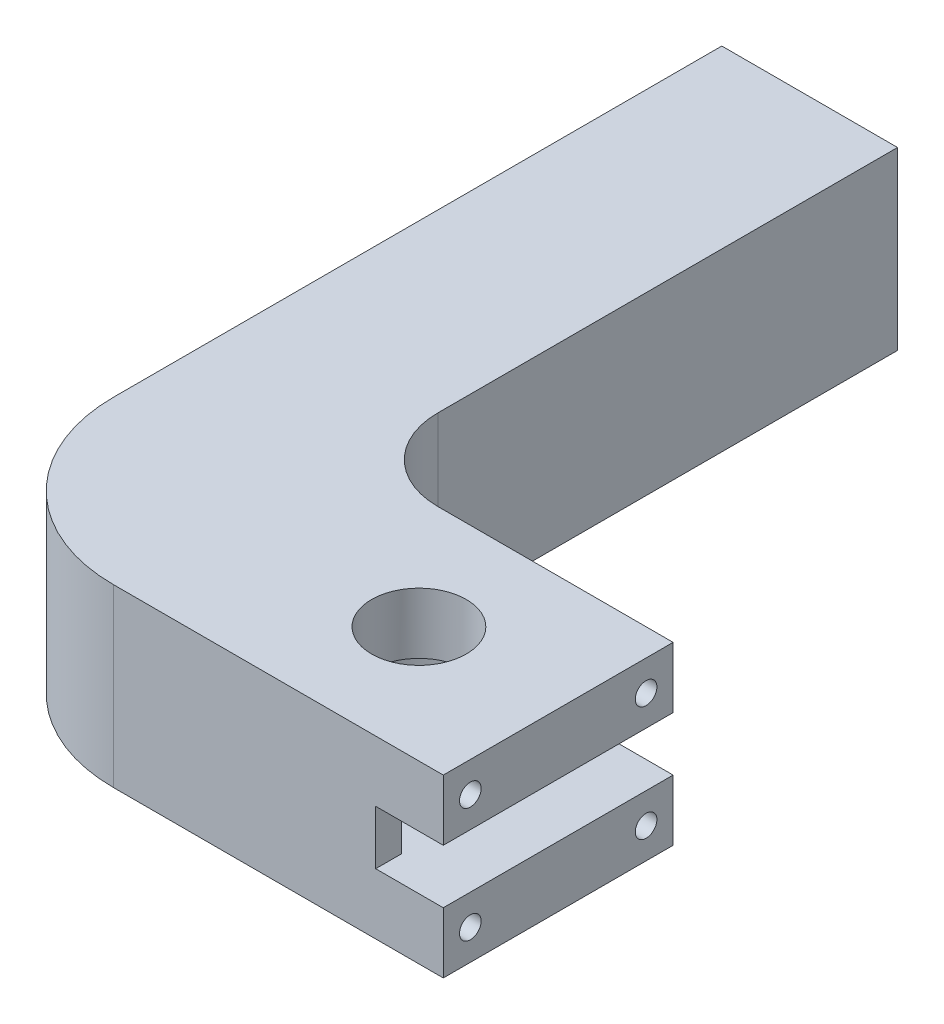
SolidWorks part; units mm, degrees
ref_plane "Front Plane" through (0, 0, 0) normal (0, 0, 1) x (1, 0, 0)
ref_plane "Top Plane" through (0, 0, 0) normal (0, 1, 0) x (1, 0, 0)
ref_plane "Right Plane" through (0, 0, 0) normal (1, 0, 0) x (0, 0, -1)
ref_plane "Plane1" through (0, 571.5, 0) normal (0, 1, 0) x (1, 0, 0)
sketch "Sketch1" plane through (0, 571.5, 0) normal (0, 1, 0) x (1, 0, 0)
  line L0 (3987.8, -7239) -> (3987.8, -5080)
  line L1 (3987.8, -5080) -> (0, -5080)
  line L2 (0, -5080) -> (0, -7239)
  line L3 (0, -7239) -> (3987.8, -7239)
extrude "Boss-Extrude1" add sketch "Sketch1" against normal blind 571.5
sketch "Sketch2" plane through (0, 571.5, 0) normal (0, 1, 0) x (-1, 0, 0)
  line L0 (-3987.8, 5321.3) -> (-3447.3581, 5321.3)
  line L1 (-3302, 6985) -> (-3987.8, 6985)
  line L2 (-3987.8, 6985) -> (-3987.8, 7239)
  line L3 (-3987.8, 7239) -> (0, 7239)
  line L4 (0, 7239) -> (0, 5080)
  line L5 (0, 5080) -> (-3987.8, 5080)
  line L6 (-3987.8, 5080) -> (-3987.8, 5321.3)
  arc A0 (-3447.3581, 5321.3) -> (-3302, 6985) centre (-3302, 6146.8) ccw
extrude "Boss-Extrude2" add sketch "Sketch2" along normal blind 508
sketch "Sketch3" plane through (0, 1079.5, 0) normal (0, 1, 0) x (-1, 0, 0)
  line L0 (-3987.8, 7239) -> (0, 7239)
  line L1 (0, 7239) -> (0, 5080)
  line L2 (0, 5080) -> (-3987.8, 5080)
  line L3 (-3987.8, 5080) -> (-3987.8, 7239)
extrude "Boss-Extrude3" add sketch "Sketch3" along normal blind 571.5
sketch "Sketch4" plane through (0, 0, 6985) normal (0, 0, -1) x (-1, 0, 0)
  line L0 (-3987.8, 571.5) -> (-3302, 571.5)
  line L1 (-3302, 571.5) -> (-3302, 1079.5)
  line L2 (-3302, 1079.5) -> (-3987.8, 1079.5)
  line L3 (-3987.8, 1079.5) -> (-3987.8, 571.5)
extrude "Cut-Extrude1" cut sketch "Sketch4" against normal blind 12.7
sketch "Sketch5" plane through (3987.8, 0, 0) normal (1, 0, 0) x (0, 0, -1)
  line L0 (-7239, 571.5) -> (-5080, 571.5)
  line L1 (-5080, 571.5) -> (-5080, 0)
  line L2 (-5080, 0) -> (-7239, 0)
  line L3 (-7239, 0) -> (-7239, 571.5)
extrude "Boss-Extrude4" add sketch "Sketch5" along normal blind 635
sketch "Sketch6" plane through (3987.8, 0, 0) normal (1, 0, 0) x (0, 0, -1)
  line L0 (-5080, 1079.5) -> (-7239, 1079.5)
  line L1 (-7239, 1079.5) -> (-7239, 1651)
  line L2 (-7239, 1651) -> (-5080, 1651)
  line L3 (-5080, 1651) -> (-5080, 1079.5)
extrude "Boss-Extrude5" add sketch "Sketch6" along normal blind 635
sketch "Sketch7" plane through (0, 0, 5080) normal (0, 0, -1) x (-1, 0, 0)
  line L0 (-1651, 0) -> (-1651, 1651)
  line L1 (-1651, 1651) -> (0, 1651)
  line L2 (0, 1651) -> (0, 0)
  line L3 (0, 0) -> (-1651, 0)
extrude "Boss-Extrude6" add sketch "Sketch7" along normal blind 5080
hole_wizard "Hole1" positions "Sketch9" profile "Sketch8" legacy
sketch "Sketch9" plane through (4622.8, 0, 0) normal (1, 0, 0) x (0, 0, -1)
  point P0 (-6985, 285.75)
  point P1 (-5334, 285.75)
  point P2 (-5334, 1365.25)
  point P3 (-6985, 1365.25)
sketch "Sketch8" plane through (4622.8, 285.75, 6985) normal (0, 1, 0) x (0, 0, -1)
  line L0 (0, 0) -> (0, 508)
  line L1 (0, 508) -> (101.6, 508)
  line L2 (101.6, 508) -> (101.6, 0)
  line L3 (101.6, 0) -> (0, 0)
  line L4 (0, 110) -> (0, -10) construction
  dimension "Diameter" = 203.2
  dimension "Depth" = 508
hole_wizard "Hole2" positions "Sketch11" profile "Sketch10" legacy
sketch "Sketch11" plane through (0, 0, 0) normal (0, -1, 0) x (-1, 0, 0)
  point P0 (-3302, -6146.8)
sketch "Sketch10" plane through (3302, 0, 6146.8) normal (1, 0, 0) x (0, 0, -1)
  line L0 (0, 0) -> (0, 571.5)
  line L1 (0, 571.5) -> (444.5, 571.5)
  line L2 (444.5, 571.5) -> (444.5, 0)
  line L3 (444.5, 0) -> (0, 0)
  line L4 (0, 110) -> (0, -10) construction
  dimension "Diameter" = 889
  dimension "Depth" = 571.5
hole_wizard "Hole3" positions "Sketch13" profile "Sketch12" legacy
sketch "Sketch13" plane through (0, 1651, 0) normal (0, 1, 0) x (1, 0, 0)
  point P0 (3302, -6146.8)
sketch "Sketch12" plane through (3302, 1651, 6146.8) normal (1, 0, 0) x (0, 0, 1)
  line L0 (0, 0) -> (0, 571.5)
  line L1 (0, 571.5) -> (444.5, 571.5)
  line L2 (444.5, 571.5) -> (444.5, 0)
  line L3 (444.5, 0) -> (0, 0)
  line L4 (0, 110) -> (0, -10) construction
  dimension "Diameter" = 889
  dimension "Depth" = 571.5
fillet "Fillet1" radius 762 1 edges at (1651, 825.5, 5080)
fillet "Fillet2" radius 1524 1 edges at (0, 825.5, 7239)
